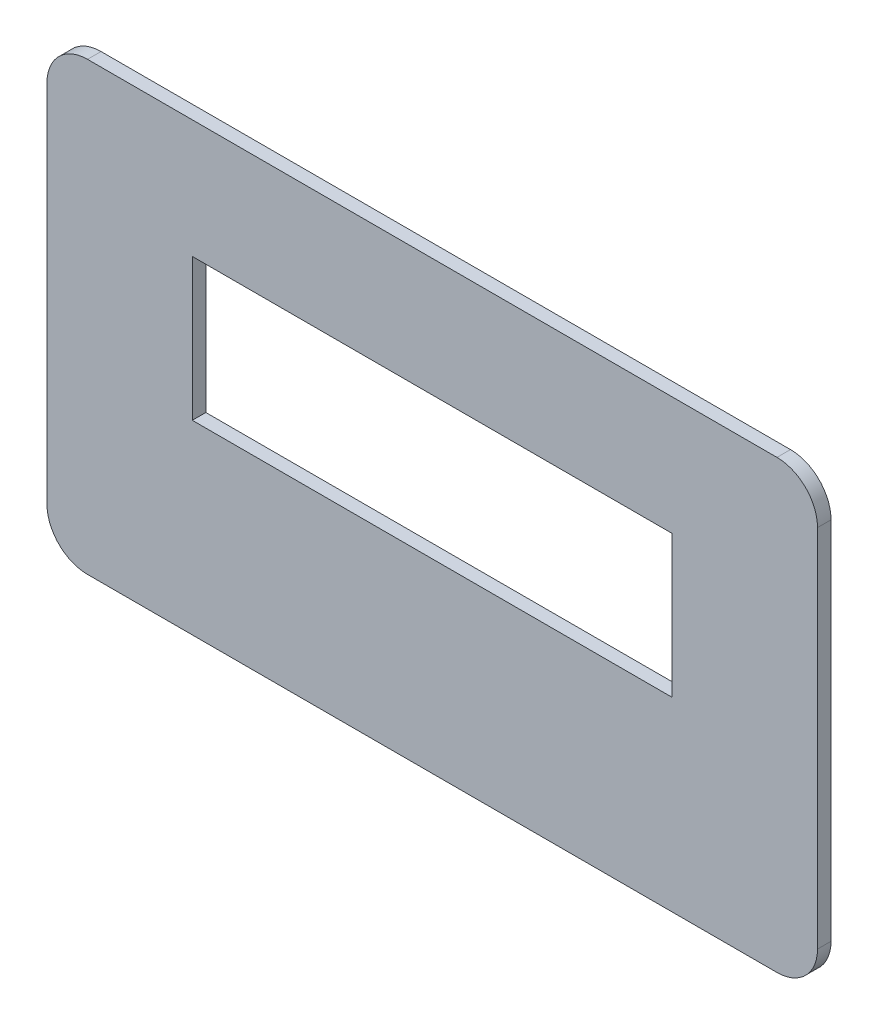
SolidWorks part; units mm, degrees
ref_plane "Front Plane" through (0, 0, 0) normal (0, 0, 1) x (1, 0, 0)
ref_plane "Top Plane" through (0, 0, 0) normal (0, 1, 0) x (1, 0, 0)
ref_plane "Right Plane" through (0, 0, 0) normal (1, 0, 0) x (0, 0, -1)
sketch "Sketch1" plane through (0, 0, 0) normal (0, 0, 1) x (1, 0, 0)
  line L1 (51, 33) -> (-51, 33)
  line L2 (57, 27) -> (57, -27)
  line L3 (51, -33) -> (-51, -33)
  line L4 (-57, 27) -> (-57, -27)
  line L5 (57, 33) -> (-57, -33) construction
  line L6 (57, -33) -> (-57, 33) construction
  line L7 (-35.5, -5.5) -> (35.5, -5.5)
  line L8 (-35.5, -5.5) -> (-35.5, 15.5)
  line L9 (-35.5, 15.5) -> (35.5, 15.5)
  line L10 (35.5, -5.5) -> (35.5, 15.5)
  arc A0 (-51, -33) -> (-57, -27) centre (-51, -27) cw
  arc A1 (51, -33) -> (57, -27) centre (51, -27) ccw
  arc A2 (57, 27) -> (51, 33) centre (51, 27) ccw
  arc A3 (-57, 27) -> (-51, 33) centre (-51, 27) cw
  point P0 (0, 0)
  point P6 (0, 0)
  point P23 (0, 5)
  dimension "D1" = 6
  dimension "D2" = 114
  dimension "D3" = 71
  dimension "D4" = 21
  dimension "D5" = 66
  dimension "D6" = 17.5
extrude "Boss-Extrude1" add sketch "Sketch1" along normal blind 2
